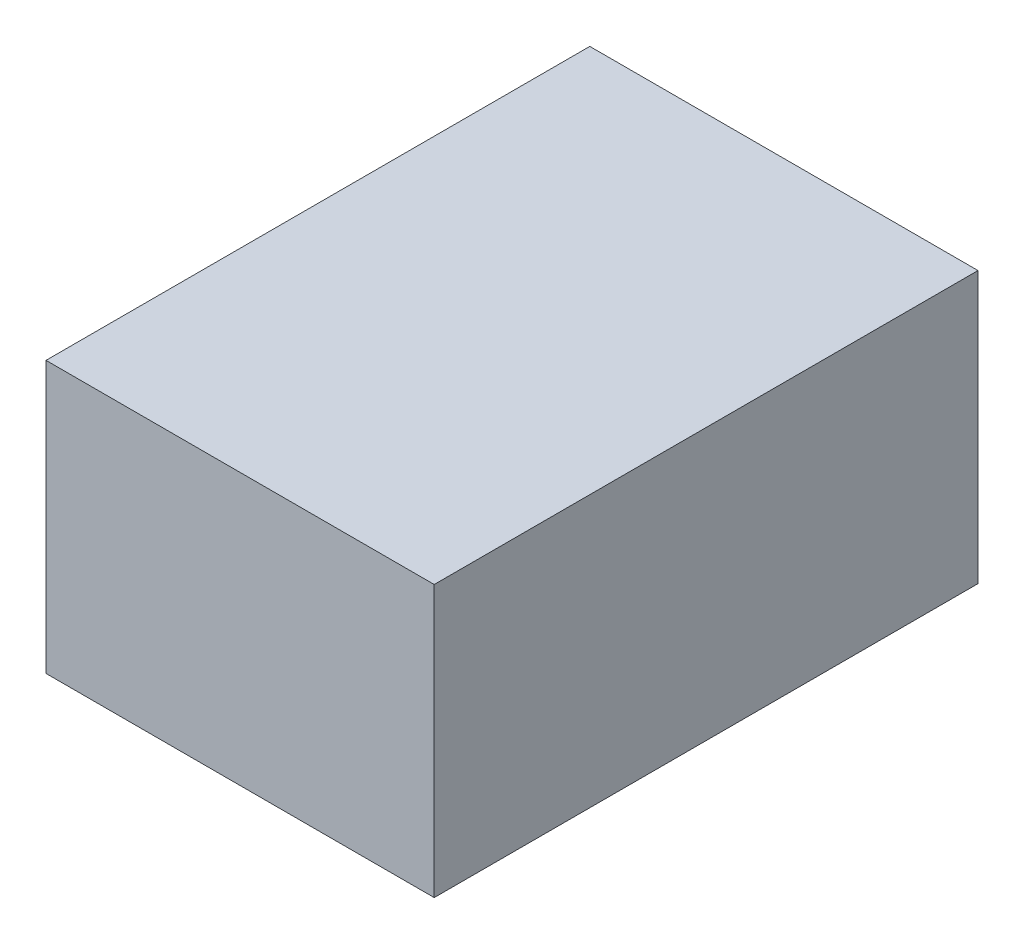
SolidWorks part; units mm, degrees
material "Epoxy, renforcé"
ref_plane "Plan de face" through (0, 0, 0) normal (0, 0, 1) x (1, 0, 0)
ref_plane "Plan de dessus" through (0, 0, 0) normal (0, 1, 0) x (1, 0, 0)
ref_plane "Plan de droite" through (0, 0, 0) normal (1, 0, 0) x (0, 0, -1)
sketch "Esquisse1" plane through (0, 0, 0) normal (0, 1, 0) x (1, 0, 0)
  line L1 (0, 0) -> (27.2, 0)
  line L2 (0, 0) -> (0, 38.1)
  line L3 (0, 38.1) -> (27.2, 38.1)
  line L4 (27.2, 0) -> (27.2, 38.1)
  dimension "D1" = 38.1
  dimension "D2" = 27.2
extrude "Boss.-Extru.1" add sketch "Esquisse1" along normal blind 19
